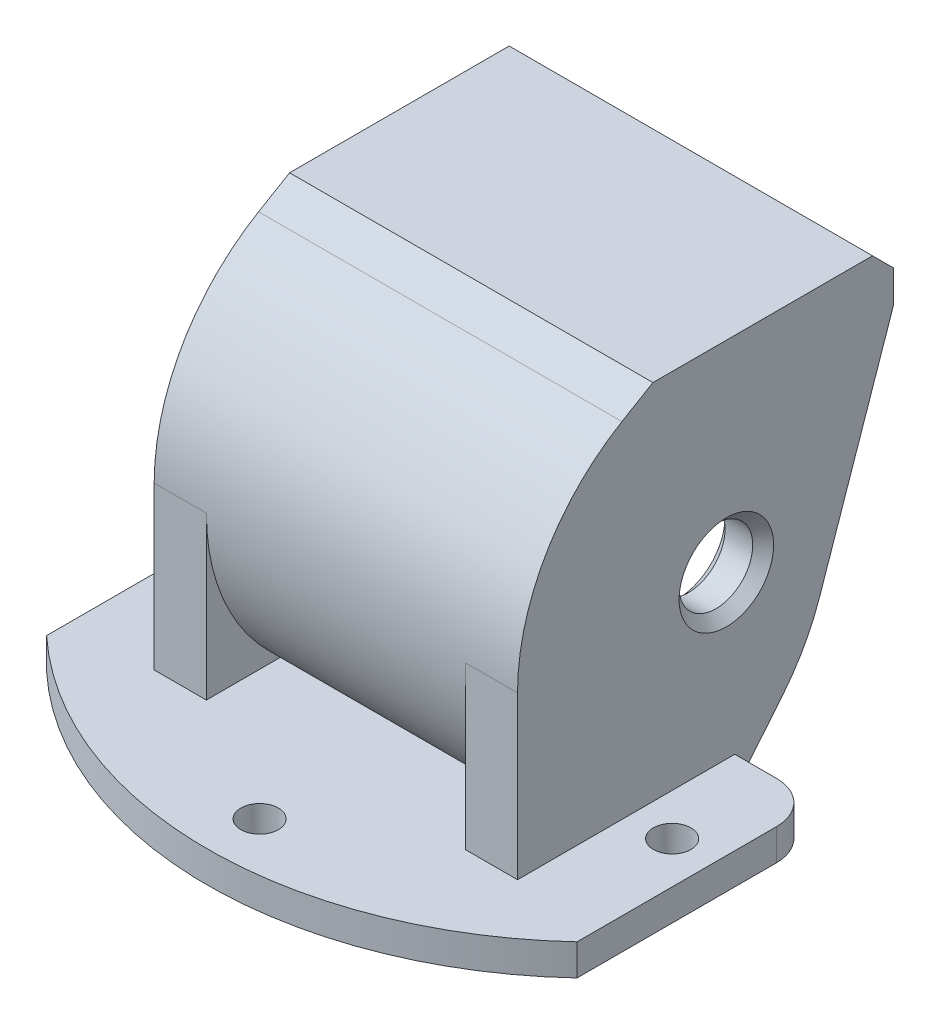
SolidWorks part; units mm, degrees
ref_plane "Front Plane" through (0, 0, 0) normal (0, 0, 1) x (1, 0, 0)
ref_plane "Top Plane" through (0, 0, 0) normal (0, 1, 0) x (1, 0, 0)
ref_plane "Right Plane" through (0, 0, 0) normal (1, 0, 0) x (0, 0, -1)
sketch "Sketch1" plane through (0, 0, 0) normal (1, 0, 0) x (0, 0, -1)
  line L0 (0, 17.5) -> (0, -17.5) construction
  line L1 (0, 17.5) -> (-10, 17.5)
  line L2 (10, 17.5) -> (10, -17.5) construction
  line L3 (0, -17.5) -> (-10, -17.5)
  line L4 (-10, 17.5) -> (-10, -17.5) construction
  line L5 (0, 0) -> (10, 0) construction
  line L6 (0, 0) -> (-10, 0) construction
  line L7 (0, 0) -> (-10, 0) construction
  line L8 (-10, 0) -> (-20, 0) construction
  arc A0 (0, -17.5) -> (0, 17.5) centre (-10.3125, 0) ccw
  arc A1 (-10, 17.5) -> (-10, -17.5) centre (0.3125, 0) ccw
  dimension "D3" = 20
  dimension "D1" = 35
extrude "Boss-Extrude1" add sketch "Sketch1" against normal mid plane 34.8
sketch "Sketch2" plane through (0, 0, 0) normal (1, 0, 0) x (0, 0, -1)
  line L0 (0, 17.5) -> (-10, 17.5) construction
  line L1 (-10, -17.5) -> (0, -17.5) construction
  line L2 (-16, 0) -> (-20, 0) construction
  line L4 (-10, -17.5) -> (0, -17.5)
  line L5 (0, 17.5) -> (-10, 17.5)
  line L6 (-6, -17.5) -> (0, -17.5)
  line L7 (0, 17.5) -> (-6, 17.5)
  arc A0 (-6, 17.5) -> (-6, -17.5) centre (4.3125, 0) ccw
  arc A1 (-10, 17.5) -> (-10, -17.5) centre (0.3125, 0) ccw construction
  arc A4 (-10, 17.5) -> (-10, -17.5) centre (0.3125, 0) ccw
  arc A5 (0, -17.5) -> (0, 17.5) centre (-10.3125, 0) ccw
  arc A7 (0, -17.5) -> (0, 17.5) centre (-10.3125, 0) ccw
  dimension "D1" = 0
  dimension "D2" = 4
extrude "Cut-Extrude1" cut sketch "Sketch2" along normal mid plane 25.5
sketch "Sketch3" plane through (0, 0, 0) normal (1, 0, 0) x (0, 0, -1)
  line L0 (-9.5, -17.5) -> (-9.5, -24)
  line L1 (-10, -17.5) -> (0, -17.5) construction
  line L2 (-0.5, -24) -> (-0.5, -17.5)
  line L3 (-0.5, -17.5) -> (-9.5, -17.5)
  line L4 (-5, -28.5) -> (-5, -17.5) construction
  arc A0 (-9.5, -24) -> (-0.5, -24) centre (-5, -24) ccw
  dimension "D1" = 9
  dimension "D2" = 6.5
extrude "Boss-Extrude2" add sketch "Sketch3" along normal mid plane 10
sketch "Sketch4" plane through (17.4, 0, 0) normal (1, 0, 0) x (0, 0, -1)
  line L0 (-13.4374, -9.8761) -> (0.9816, -18.201)
  line L1 (0.8089, -18.5) -> (-8.303, -18.5)
  line L4 (-13.4374, -9.8761) -> (-17.4374, -9.8761)
  line L5 (0.8089, -18.5) -> (0.9816, -18.201)
  line L8 (0, 0) -> (14.9634, 0.0217) construction
  line L9 (14.9634, 0.0217) -> (14.9855, -15.25) construction
  line L10 (69.9999, 0.1014) -> (0, 0) construction
  line L12 (-10, -17.5) -> (-8.303, -18.5)
  line L13 (0.9816, -18.201) -> (8.6174, -4.9753) construction
  line L14 (0, 0) -> (8.6174, -4.9753) construction
  line L15 (0, 0) -> (-8.348, 0) construction
  line L16 (-10, -17.5) -> (0, -17.5) construction
  arc A0 (-10, 17.5) -> (-10, -17.5) centre (0.3125, 0) ccw construction
  arc A2 (-6, 17.5) -> (-6, -17.5) centre (4.3125, 0) ccw construction
  arc A3 (-6, 17.5) -> (-6, -17.5) centre (4.3125, 0) ccw construction
  arc A4 (-17.4374, -9.8761) -> (-10, -17.5) centre (0.3125, 0) ccw
  dimension "D1" = 30
  dimension "D2" = 0.299
  dimension "D3" = 1
extrude "Boss-Extrude3" add sketch "Sketch4" against normal up to surface (34.8 mm away) up to face at (-17.4, 0, 5)
sketch "Sketch5" plane through (17.4, 0, 0) normal (1, 0, 0) x (0, 0, -1)
  line L4 (-8.303, -18.5) -> (0.8089, -18.5) construction
  line L5 (5.426, -12.8412) -> (0.8089, -18.5)
  line L6 (0.8089, -18.5) -> (0.9816, -18.201) construction
  line L7 (0.8089, -18.5) -> (-1.1911, -18.5)
  line L8 (-1.1911, -18.5) -> (-1.1911, -17.5)
  line L9 (-1.1911, -17.5) -> (5.426, -12.8412)
  arc A3 (0, -17.5) -> (0, 17.5) centre (-10.3125, 0) ccw construction
  dimension "D1" = 1
  dimension "D2" = 2
extrude "Boss-Extrude4" add sketch "Sketch5" against normal up to surface (4.65 mm away) up to face at (12.75, -1.6725, 3.0481)
sketch "Sketch6" plane through (-17.4, 0, 0) normal (-1, 0, 0) x (0, 0, 1)
  line L2 (-5.426, -12.8412) -> (-0.8089, -18.5)
  line L3 (-5.426, -12.8412) -> (-0.8089, -18.5)
  line L4 (-0.8089, -18.5) -> (1.1911, -18.5)
  line L5 (-0.8089, -18.5) -> (1.1911, -18.5)
  line L12 (1.1911, -18.5) -> (1.1911, -17.5)
  line L13 (1.1911, -18.5) -> (1.1911, -17.5)
  line L14 (1.1911, -17.5) -> (-5.426, -12.8412)
  line L15 (1.1911, -17.5) -> (-5.426, -12.8412)
  dimension "D1" = 0
extrude "Boss-Extrude5" add sketch "Sketch6" against normal up to surface (4.65 mm away) up to face at (-12.75, -1.6725, 3.0481)
sketch "Sketch7" plane through (17.4, 0, 0) normal (1, 0, 0) x (0, 0, -1)
  line L0 (-10, 17.5) -> (-7.0303, 19.25)
  line L1 (-7.0303, 19.25) -> (16, 19.25)
  line L2 (16, 19.25) -> (16, 14.1219)
  line L3 (0, 0) -> (1.3291, 15.192) construction
  line L4 (3.1052, 15.25) -> (-13.1052, 15.25)
  line L6 (0, 0) -> (0, 15.25) construction
  line L7 (69.7336, -6.1009) -> (0, 0) construction
  line L8 (86.3842, 7.7506) -> (31.7938, 12.5267) construction
  line L9 (0, 17.5) -> (-10, 17.5) construction
  line L10 (3.1052, 15.25) -> (16, 14.1219)
  line L11 (0, 17.5) -> (-10, 17.5) construction
  line L13 (10, 0) -> (10, 11.0966) construction
  line L14 (0, 0) -> (69.7336, 0) construction
  arc A0 (-10, 17.5) -> (-10, -17.5) centre (0.3125, 0) ccw construction
  arc A1 (-10, 17.5) -> (-13.1052, 15.25) centre (0.3125, 0) ccw
  arc A3 (5.426, -12.8412) -> (0, 17.5) centre (-10.3125, 0) ccw construction
  dimension "D1" = 5
  dimension "D2" = 4
  dimension "D3" = 6
extrude "Boss-Extrude6" add sketch "Sketch7" against normal up to surface (34.8 mm away) up to face at (-17.4, -5.1825, 4.1831)
sketch "Sketch8" plane through (17.4, 0, 0) normal (1, 0, 0) x (0, 0, -1)
  line L0 (16, 14.1219) -> (8.9027, -6.5858)
  line L2 (3.1052, 15.25) -> (16, 14.1219)
  arc A0 (5.426, -12.8412) -> (3.1052, 15.25) centre (-10.3125, 0) ccw construction
  arc A1 (8.9027, -6.5858) -> (3.1052, 15.25) centre (-10.3125, 0) ccw
extrude "Boss-Extrude7" add sketch "Sketch8" against normal up to surface (4.65 mm away) up to face at (12.75, -4.6143, 1.8315)
sketch "Sketch9" plane through (-17.4, 0, 0) normal (-1, 0, 0) x (0, 0, 1)
  line L2 (-16, 14.1219) -> (-8.9027, -6.5858)
  line L3 (-3.1052, 15.25) -> (-16, 14.1219)
  line L4 (-16, 14.1219) -> (-8.9027, -6.5858)
  line L5 (-3.1052, 15.25) -> (-16, 14.1219)
  arc A1 (-3.1052, 15.25) -> (-8.9027, -6.5858) centre (10.3125, 0) ccw
  arc A2 (-3.1052, 15.25) -> (-8.9027, -6.5858) centre (10.3125, 0) ccw
  dimension "D1" = 0
extrude "Boss-Extrude8" add sketch "Sketch9" against normal up to surface (4.65 mm away) up to face at (-12.75, -4.6143, 1.8315)
chamfer "Chamfer2" distance 2 angle 45 1 edges at (0, 19.25, -16)
sketch "Sketch10" plane through (17.4, 0, 0) normal (1, 0, 0) x (0, 0, -1)
  circle A0 centre (0, 0) radius 3.175 construction
  circle A1 centre (0, 0) radius 3.525
  dimension "D1" = 6.35
  dimension "D2" = 0.35
extrude "Cut-Extrude2" cut sketch "Sketch10" against normal through all
sketch "Sketch11" plane through (0, 0, 0) normal (1, 0, 0) x (0, 0, -1)
  line L3 (-9.5, -17.5) -> (-9.5, -24)
  line L4 (-0.5, -24) -> (-0.5, -17.5)
  line L5 (-0.5, -17.5) -> (-9.5, -17.5)
  line L6 (-9.5, -17.5) -> (-9.5, -24)
  line L7 (-0.5, -24) -> (-0.5, -17.5)
  line L8 (-0.5, -17.5) -> (-9.5, -17.5)
  arc A1 (-9.5, -24) -> (-0.5, -24) centre (-5, -24) ccw
  arc A2 (-9.5, -24) -> (-0.5, -24) centre (-5, -24) ccw
  dimension "D1" = 0
extrude "Cut-Extrude3" cut sketch "Sketch11" against normal mid plane 0.762
chamfer "Chamfer3" [suppressed] distance 5 angle 45
sketch "Sketch12" plane through (0, -18.5, 0) normal (0, -1, 0) x (1, 0, 0)
  line L0 (-17.4, -0.8089) -> (-21.4, -0.8089)
  line L2 (21.4, -0.8089) -> (17.4, -0.8089)
  line L4 (-25.4, 22.303) -> (25.4, 22.303) construction
  line L8 (-25.4, 3.1911) -> (-25.4, 22.303)
  line L9 (25.4, 22.303) -> (25.4, 3.1911)
  line L10 (-17.4, 8.303) -> (-25.4, 8.303) construction
  line L11 (0, 22.303) -> (0, 32.303) construction
  line L12 (-17.4, -0.8089) -> (-17.4, 8.303) construction
  line L13 (17.4, 8.303) -> (25.4, 8.303) construction
  line L14 (17.4, 8.303) -> (17.4, -0.8089) construction
  line L15 (-17.4, -0.8089) -> (-17.4, 8.303)
  line L16 (17.4, 8.303) -> (17.4, -0.8089)
  line L17 (17.4, 8.303) -> (-17.4, 8.303)
  arc A0 (-21.4, -0.8089) -> (-25.4, 3.1911) centre (-21.4, 3.1911) cw
  arc A1 (25.4, 3.1911) -> (21.4, -0.8089) centre (21.4, 3.1911) cw
  arc A2 (-25.4, 22.303) -> (25.4, 22.303) centre (0, -4.955) cw
  dimension "D2" = 4
  dimension "D1" = 8
  dimension "D3" = 10
  dimension "D4" = 14
extrude "Boss-Extrude9" add sketch "Sketch12" against normal blind 3
sketch "Sketch13" plane through (-17.4, 0, 0) normal (-1, 0, 0) x (0, 0, 1)
  line L0 (20, -15.5) -> (12.8156, -15.5) construction
  line L1 (20, -15.5) -> (20, 0)
  line L3 (12.8156, -15.5) -> (12.8156, -23.5)
  line L4 (12.8156, -23.5) -> (20, -23.5)
  line L5 (20, -23.5) -> (20, -15.5)
  line L6 (22.303, -18.5) -> (3.1911, -18.5) construction
  arc A0 (20, 0) -> (12.8156, -15.5) centre (-0.3125, 0) cw
  arc A1 (12.8156, -15.5) -> (10, 17.5) centre (-0.3125, 0) ccw construction
  dimension "D1" = 5
extrude "Boss-Extrude10" add sketch "Sketch13" against normal blind 5
mirror "Mirror1" about plane through (0, 0, 0) normal (1, 0, 0) of "Boss-Extrude10"
hole_wizard "M3 Clearance Hole1" positions "Sketch14" profile "Sketch15" hole size "M3" standard "ANSI Metric" end condition through all
sketch "Sketch14" plane through (0, -15.5, 0) normal (0, 1, 0) x (1, 0, 0)
  line L3 (0, -27.303) -> (0, -32.303) construction
  line L4 (-21.4, 0.8089) -> (-21.4, -9.1911) construction
  line L6 (21.4, 0.8089) -> (21.4, -9.1911) construction
  arc A1 (-25.4, -22.303) -> (25.4, -22.303) centre (0, 4.955) ccw construction
  point P10 (0, -27.303)
  point P34 (-21.4, -9.1911)
  point P36 (21.4, -9.1911)
  dimension "D1" = 5
  dimension "D2" = 10
sketch "Sketch15" plane through (0, -15.5, 27.303) normal (1, 0, 0) x (0, 0, 1)
  line L0 (0, 0) -> (0, 13)
  line L1 (0, 13) -> (1.8, 13)
  line L2 (1.8, 13) -> (1.8, 0)
  line L5 (1.8, 0) -> (0, 0)
  line L11 (0, -6.35) -> (0, 107.95) construction
  dimension "Thru Hole Dia." = 3.6
  dimension "Thru Hole Depth" = 13
hole_wizard "M3 Clearance Hole2" positions "Sketch16" profile "Sketch17" hole size "M3" standard "ANSI Metric" end condition through all
sketch "Sketch16" plane through (5, 0, 0) normal (1, 0, 0) x (0, 0, -1)
  point P0 (-5, -24)
sketch "Sketch17" plane through (5, -24, 5) normal (0, 1, 0) x (0, 0, -1)
  line L0 (0, 0) -> (0, 30.4)
  line L1 (0, 30.4) -> (1.8, 30.4)
  line L2 (1.8, 30.4) -> (1.8, 0)
  line L5 (1.8, 0) -> (0, 0)
  line L11 (0, -6.35) -> (0, 107.95) construction
  dimension "Thru Hole Dia." = 3.6
  dimension "Thru Hole Depth" = 30.4
chamfer "Chamfer5" distance 1 angle 45 4 edges at (17.4, 0, -3.525) (-12.75, 0, -3.525) (12.75, 0, -3.525) (-17.4, 0, -3.525)
sketch "Sketch18" plane through (0, 0, 0) normal (1, 0, 0) x (0, 0, -1)
  line L0 (0.9816, -18.201) -> (-13.4374, -9.8761)
  line L1 (-0.2321, -17.5002) -> (-13.4374, -9.8761) construction
  line L2 (-11.421, -18.5) -> (-0.5, -18.5) construction
  line L3 (-3.1911, -18.5) -> (-22.303, -18.5) construction
  line L4 (-0.5, -18.5) -> (1.4995, -18.5)
  line L5 (1.4995, -18.5) -> (-0.2321, -17.5002)
  arc A0 (-0.2321, -17.5002) -> (-0.5, -18.5) centre (-0.5, -17.9642) cw
extrude "Cut-Extrude4" cut sketch "Sketch18" against normal up to surface and the other way up to surface up to face at (-12.75, 0, -4.525) other way up to face at (12.75, 0, -4.525)
chamfer "Chamfer6" distance 1 angle 45 8 edges at (-14.9, -23.5, 20) (-12.4, -23.5, 16.4078) (-14.9, -23.5, 12.8156) (-17.4, -23.5, 16.4078) (14.9, -23.5, 12.8156) (12.4, -23.5, 16.4078) (14.9, -23.5, 20) (17.4, -23.5, 16.4078)
